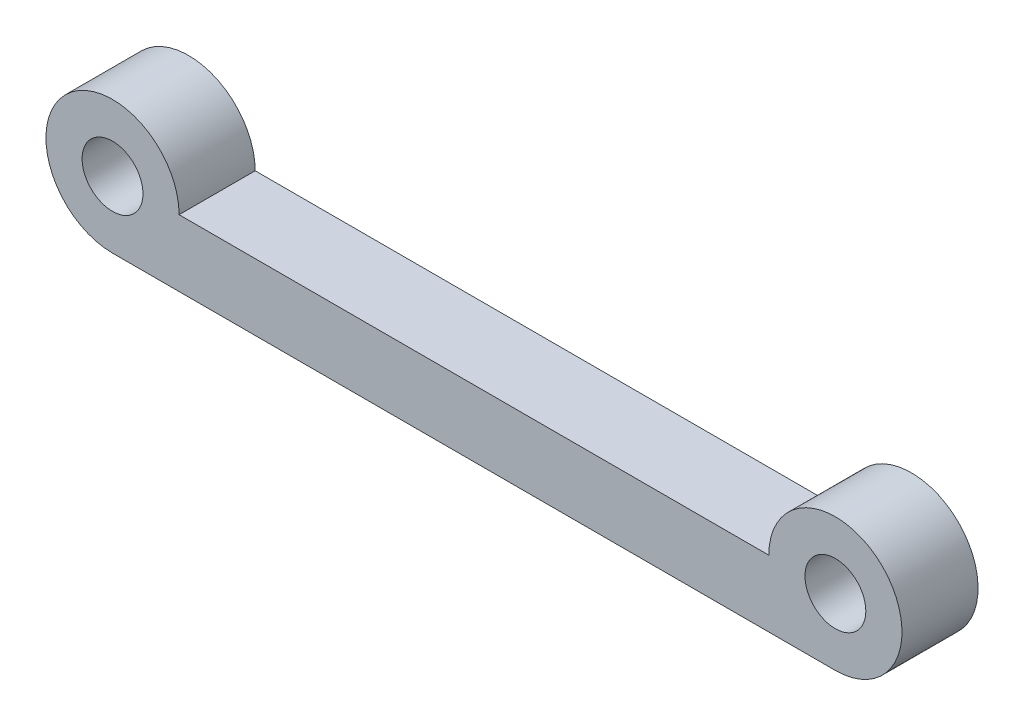
SolidWorks part; units mm, degrees
ref_plane "正面" through (0, 0, 0) normal (0, 0, 1) x (1, 0, 0)
ref_plane "平面" through (0, 0, 0) normal (0, 1, 0) x (1, 0, 0)
ref_plane "右側面" through (0, 0, 0) normal (1, 0, 0) x (0, 0, -1)
sketch "ｽｹｯﾁ1" plane through (0, 0, 0) normal (0, 0, 1) x (1, 0, 0)
  line L0 (0, -3.5) -> (38, -3.5)
  line L1 (3.5, 0) -> (34.5, 0)
  arc A0 (3.5, 0) -> (0, -3.5) centre (0, 0) ccw
  arc A1 (38, -3.5) -> (34.5, 0) centre (38, 0) ccw
  circle A2 centre (0, 0) radius 1.6
  circle A3 centre (38, 0) radius 1.6
  dimension "D3" = 7
  dimension "D4" = 7
  dimension "D2" = 3.2
  dimension "D5" = 3.2
  dimension "D1" = 38
extrude "ﾎﾞｽ - 押し出し1" add sketch "ｽｹｯﾁ1" along normal blind 4
